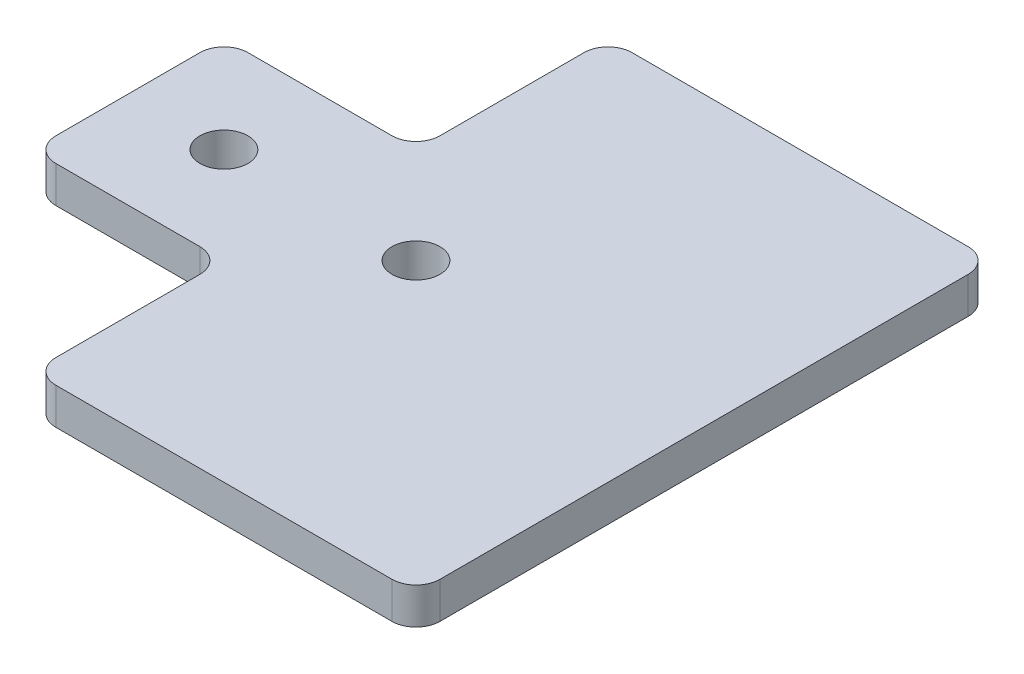
SolidWorks part; units mm, degrees
material "6061-T6 (SS)"
ref_plane "Front Plane" through (0, 0, 0) normal (0, 0, 1) x (1, 0, 0)
ref_plane "Top Plane" through (0, 0, 0) normal (0, 1, 0) x (1, 0, 0)
ref_plane "Right Plane" through (0, 0, 0) normal (1, 0, 0) x (0, 0, -1)
sketch "Sketch1" plane through (0, 0, 0) normal (0, 1, 0) x (1, 0, 0)
  line L0 (-25.4, 38.1) -> (-25.4, 12.7)
  line L1 (25.4, -38.1) -> (-25.4, -38.1)
  line L2 (25.4, -38.1) -> (25.4, 38.1)
  line L3 (25.4, 38.1) -> (-25.4, 38.1)
  line L4 (-25.4, 12.7) -> (-50.8, 12.7)
  line L5 (25.4, -38.1) -> (-25.4, 38.1) construction
  line L6 (25.4, 38.1) -> (-25.4, -38.1) construction
  line L7 (-50.8, 12.7) -> (-50.8, -12.7)
  line L8 (-50.8, -12.7) -> (-25.4, -12.7)
  line L9 (-25.4, -12.7) -> (-25.4, -38.1)
  point P0 (0, 0)
  dimension "D1" = 76.2
  dimension "D2" = 50.8
  dimension "D3" = 25.4
  dimension "D4" = 25.4
extrude "Boss-Extrude1" add sketch "Sketch1" along normal blind 4.826
fillet "Fillet1" radius 3.175 8 edges at (-50.8, 2.413, 12.7) (-50.8, 2.413, -12.7) (-25.4, 2.413, -12.7) (-25.4, 2.413, 12.7) (-25.4, 2.413, 38.1) (25.4, 2.413, 38.1) (25.4, 2.413, -38.1) (-25.4, 2.413, -38.1)
sketch "Sketch2" plane through (0, 4.826, 0) normal (0, 1, 0) x (1, 0, 0)
  line L0 (-50.8, 0) -> (25.4, 0) construction
  line L1 (-50.8, 9.525) -> (-50.8, -9.525) construction
  line L2 (25.4, -34.925) -> (25.4, 34.925) construction
  circle A0 centre (-38.1, 0) radius 3.175
  circle A1 centre (-12.7, 0) radius 3.175
  dimension "D1" = 6.35
  dimension "D2" = 25.4
  dimension "D3" = 12.7
extrude "Cut-Extrude1" cut sketch "Sketch2" against normal through all
